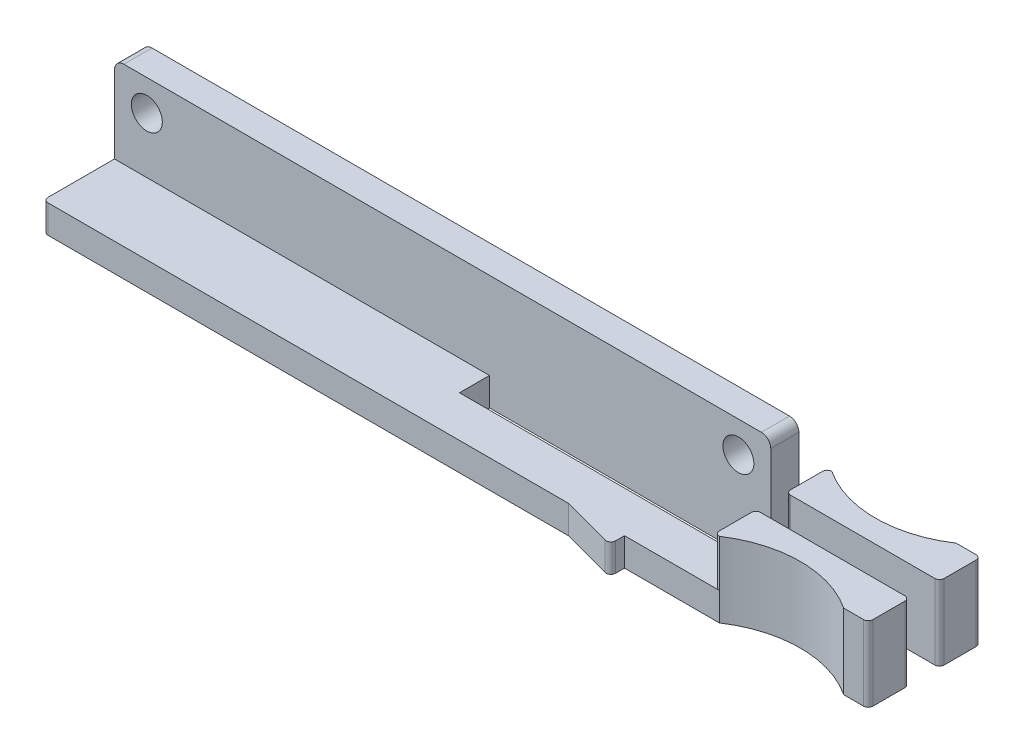
SolidWorks part; units mm, degrees
ref_plane "正面" through (0, 0, 0) normal (0, 0, 1) x (1, 0, 0)
ref_plane "平面" through (0, 0, 0) normal (0, 1, 0) x (1, 0, 0)
ref_plane "右側面" through (0, 0, 0) normal (1, 0, 0) x (0, 0, -1)
sketch "ｽｹｯﾁ2" plane through (0, 0, 0) normal (0, 1, 0) x (1, 0, 0)
  line L0 (70, 7.6) -> (40, 7.6)
  line L1 (0.5, 0) -> (56, 0)
  line L2 (0, 0.5) -> (0, 11.5)
  line L3 (0.5, 12) -> (70, 12)
  line L5 (40, 7.6) -> (40, 4.4)
  line L6 (40, 4.4) -> (70, 4.4)
  line L8 (56, 0) -> (61.3712, -1.4323)
  line L9 (62, -0.9492) -> (62, 0)
  line L10 (62, 0) -> (70, 0)
  line L11 (70, 12) -> (72.1168, 12)
  line L12 (88, 11.5) -> (88, 8.1)
  line L13 (87.5, 7.6) -> (70, 7.6)
  line L14 (70, 4.4) -> (87.5, 4.4)
  line L15 (88, 3.9) -> (88, 0.5)
  line L16 (87.5, 0) -> (85.3832, 0)
  line L17 (78.75, 12) -> (78.75, 22) construction
  line L18 (78.75, 12) -> (78.75, 10) construction
  line L19 (0, 6) -> (88, 6) construction
  line L20 (78.75, 0) -> (78.75, 2) construction
  line L21 (78.75, 0) -> (78.75, -10) construction
  line L22 (72.1168, 0) -> (70, 0)
  line L23 (85.3832, 12) -> (87.5, 12)
  arc A0 (61.3712, -1.4323) -> (62, -0.9492) centre (61.5, -0.9492) ccw
  arc A1 (72.1168, 12) -> (85.3832, 12) centre (78.75, 22) ccw
  arc A2 (72.1168, 0) -> (85.3832, 0) centre (78.75, -10) cw
  arc A3 (87.5, 12) -> (88, 11.5) centre (87.5, 11.5) cw
  arc A4 (88, 0.5) -> (87.5, 0) centre (87.5, 0.5) cw
  arc A5 (87.5, 4.4) -> (88, 3.9) centre (87.5, 3.9) cw
  arc A6 (88, 8.1) -> (87.5, 7.6) centre (87.5, 8.1) cw
  arc A7 (0.5, 0) -> (0, 0.5) centre (0.5, 0.5) cw
  arc A8 (0, 11.5) -> (0.5, 12) centre (0.5, 11.5) cw
  point P14 (62, -1.6)
  point P33 (78.75, 4.4)
  point P35 (78.75, 7.6)
  point P39 (88, 12)
  point P46 (88, 7.6)
  point P49 (0, 0)
  point P52 (0, 12)
  dimension "D8" = 0.5
  dimension "D12" = 0.5
  dimension "D13" = 0.5
  dimension "D14" = 0.5
  dimension "D1" = 70
  dimension "D2" = 18
  dimension "D3" = 3.2
  dimension "D4" = 30
  dimension "D5" = 8
  dimension "D6" = 6
  dimension "6" = 1.6
  dimension "D9" = 12
  dimension "D10" = 2
  dimension "D11" = 10
extrude "ﾎﾞｽ - 押し出し1" add sketch "ｽｹｯﾁ2" along normal blind 3
sketch "ｽｹｯﾁ4" plane through (0, 3, 0) normal (0, 1, 0) x (1, 0, 0)
  line L0 (0, 11.5) -> (0, 0.5) construction
  line L1 (70, 7.6) -> (0, 7.6)
  line L2 (70, 7.6) -> (70, 10.6)
  line L3 (70, 10.6) -> (0, 10.6)
  line L4 (0, 7.6) -> (0, 10.6)
  line L5 (40, 7.6) -> (87.5, 7.6) construction
  dimension "D1" = 3
  dimension "D2" = 70
extrude "ﾎﾞｽ - 押し出し2" add sketch "ｽｹｯﾁ4" along normal blind 9.25
sketch "ｽｹｯﾁ5" plane through (0, 0, -7.6) normal (0, 0, 1) x (1, 0, 0)
  line L0 (35, 12.25) -> (35, 8.95) construction
  line L1 (0, 12.25) -> (70, 12.25) construction
  line L2 (35, 8.95) -> (35, 3) construction
  line L4 (0.5, 3) -> (56, 3) construction
  line L7 (3.45, 8.95) -> (66.55, 8.95) construction
  circle A30 centre (3.45, 8.95) radius 1.65
  circle A31 centre (66.55, 8.95) radius 1.65
  point P9 (35, 8.95)
  point P17 (67.7, 8.7)
  point P20 (3.45, 8.7)
  dimension "D3" = 63.1
  dimension "D2" = 3.3
  dimension "D1" = 5.95
extrude "ｶｯﾄ - 押し出し1" cut sketch "ｽｹｯﾁ5" against normal up to next
fillet "ﾌｨﾚｯﾄ1" radius 1 2 edges at (70, 12.25, -9.1) (0, 12.25, -9.1)
sketch "ｽｹｯﾁ6" plane through (0, 3, 0) normal (0, 1, 0) x (1, 0, 0)
  line L0 (72.1168, 12) -> (72.1168, 7.6) construction
  line L1 (72.1168, 0) -> (72.1168, 4.4) construction
  line L23 (88, 11.5) -> (88, 8.1)
  line L24 (85.3832, 12) -> (87.5, 12)
  line L25 (88, 11.5) -> (88, 8.1)
  line L26 (85.3832, 12) -> (87.5, 12)
  line L32 (70, 7.6) -> (87.5, 7.6) construction
  line L33 (88, 3.9) -> (88, 0.5)
  line L34 (87.5, 0) -> (85.3832, 0)
  line L35 (88, 3.9) -> (88, 0.5)
  line L36 (87.5, 0) -> (85.3832, 0)
  line L39 (87.5, 4.4) -> (40, 4.4) construction
  line L41 (71.6168, 11.5) -> (71.6168, 8.1)
  line L42 (71.6168, 0.5) -> (71.6168, 3.9)
  line L43 (72.1168, 7.6) -> (87.5, 7.6)
  line L44 (72.1168, 4.4) -> (87.5, 4.4)
  arc A0 (71.6168, 3.9) -> (72.1168, 4.4) centre (72.1168, 3.9) cw
  arc A1 (71.6168, 8.1) -> (72.1168, 7.6) centre (72.1168, 8.1) ccw
  arc A36 (87.5, 7.6) -> (88, 8.1) centre (87.5, 8.1) ccw
  arc A37 (88, 11.5) -> (87.5, 12) centre (87.5, 11.5) ccw
  arc A38 (72.1168, 12) -> (85.3832, 12) centre (78.75, 22) ccw
  arc A39 (87.5, 7.6) -> (88, 8.1) centre (87.5, 8.1) ccw
  arc A40 (88, 11.5) -> (87.5, 12) centre (87.5, 11.5) ccw
  arc A41 (72.1168, 12) -> (85.3832, 12) centre (78.75, 22) ccw
  arc A48 (71.6168, 0.5) -> (72.1168, 0) centre (72.1168, 0.5) ccw
  arc A49 (72.1168, 12) -> (71.6168, 11.5) centre (72.1168, 11.5) ccw
  arc A51 (88, 3.9) -> (87.5, 4.4) centre (87.5, 3.9) ccw
  arc A52 (87.5, 0) -> (88, 0.5) centre (87.5, 0.5) ccw
  arc A53 (85.3832, 0) -> (72.1168, 0) centre (78.75, -10) ccw
  arc A54 (88, 3.9) -> (87.5, 4.4) centre (87.5, 3.9) ccw
  arc A55 (87.5, 0) -> (88, 0.5) centre (87.5, 0.5) ccw
  arc A56 (85.3832, 0) -> (72.1168, 0) centre (78.75, -10) ccw
  point P14 (71.6168, 4.4)
  point P17 (71.6168, 7.6)
  dimension "D3" = 1
  dimension "D4" = 0.5
  dimension "D1" = 0
  dimension "D2" = 0
extrude "ﾎﾞｽ - 押し出し3" add sketch "ｽｹｯﾁ6" along normal blind 5
